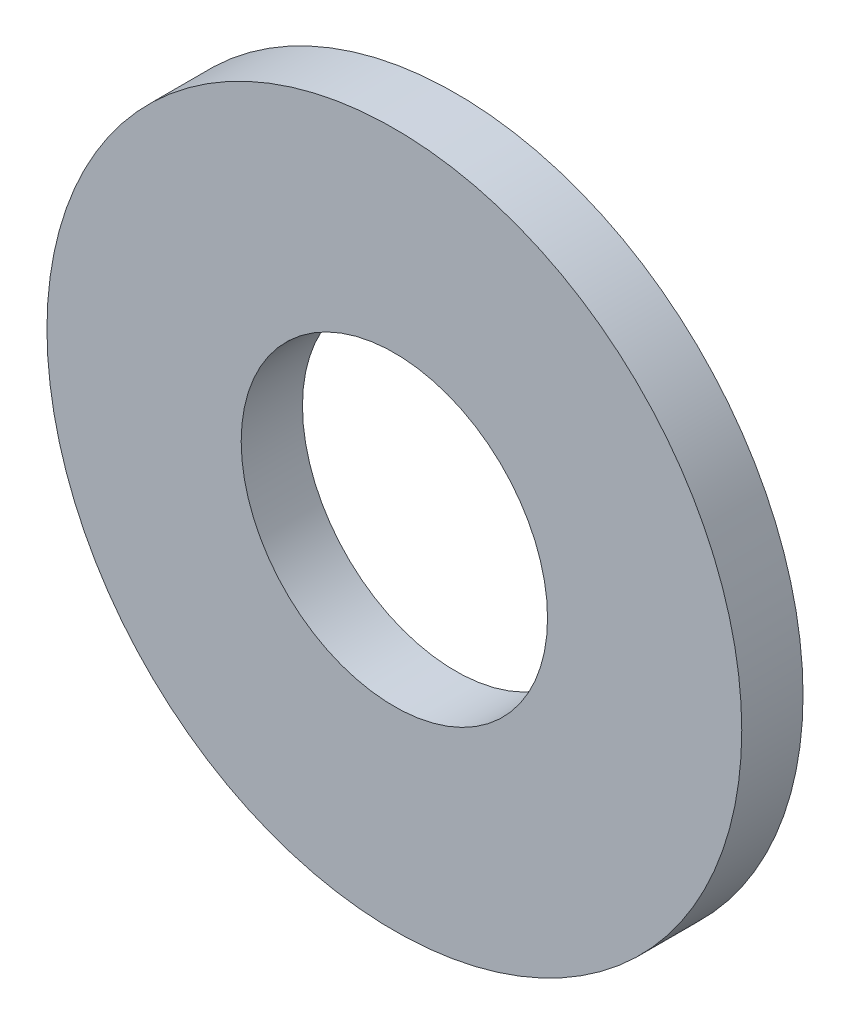
SolidWorks part; units mm, degrees
ref_plane "Front Plane" through (0, 0, 0) normal (0, 0, 1) x (1, 0, 0)
ref_plane "Top Plane" through (0, 0, 0) normal (0, 1, 0) x (1, 0, 0)
ref_plane "Right Plane" through (0, 0, 0) normal (1, 0, 0) x (0, 0, -1)
sketch "Sketch1" plane through (0, 0, 0) normal (0, 0, 1) x (1, 0, 0)
  circle A0 centre (0, 0) radius 7.2009
  dimension "D1" = 14.4018
extrude "Boss-Extrude1" add sketch "Sketch1" along normal blind 1.27
sketch "Sketch2" plane through (0, 0, 1.27) normal (0, 0, 1) x (1, 0, 0)
  circle A0 centre (0, 0) radius 3.175
  dimension "D1" = 6.35
extrude "Cut-Extrude1" cut sketch "Sketch2" against normal through all
